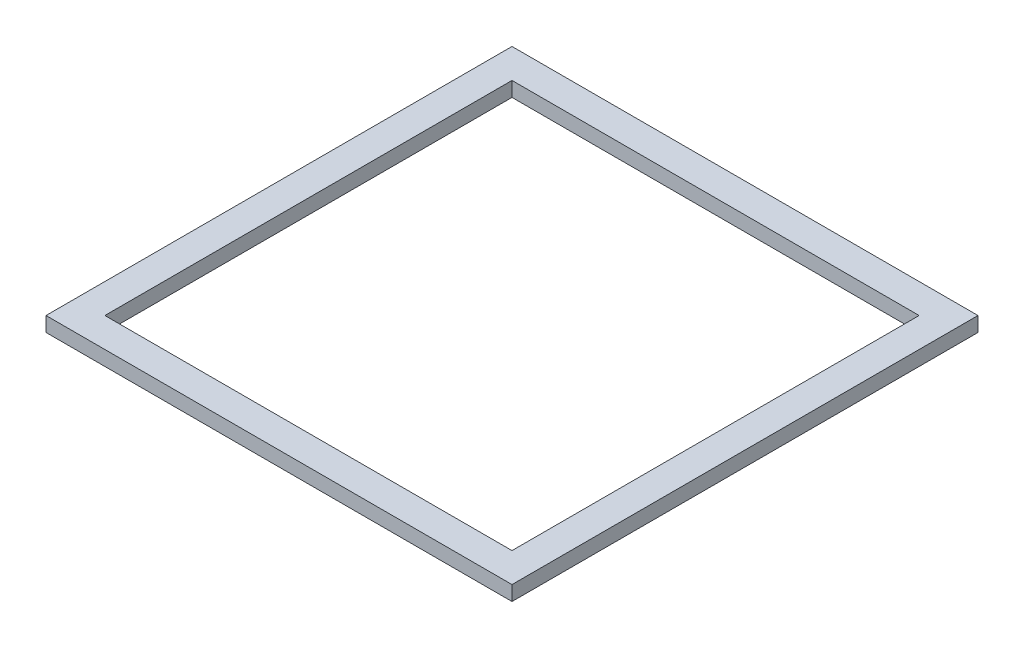
SolidWorks part; units mm, degrees
ref_plane "Front Plane" through (0, 0, 0) normal (0, 0, 1) x (1, 0, 0)
ref_plane "Top Plane" through (0, 0, 0) normal (0, 1, 0) x (1, 0, 0)
ref_plane "Right Plane" through (0, 0, 0) normal (1, 0, 0) x (0, 0, -1)
sketch "Sketch1" plane through (0, 0, 0) normal (0, 1, 0) x (1, 0, 0)
  line L0 (3, -3) -> (44.5, -3)
  line L1 (0, 0) -> (47.5, 0)
  line L2 (0, 0) -> (0, -47.5)
  line L3 (0, -47.5) -> (47.5, -47.5)
  line L4 (47.5, 0) -> (47.5, -47.5)
  line L5 (44.5, -3) -> (44.5, -44.5)
  line L6 (3, -44.5) -> (44.5, -44.5)
  line L7 (3, -3) -> (3, -44.5)
  dimension "D1" = 47.5
  dimension "D2" = 47.5
  dimension "D3" = 3
extrude "Boss-Extrude1" add sketch "Sketch1" along normal blind 1.5
